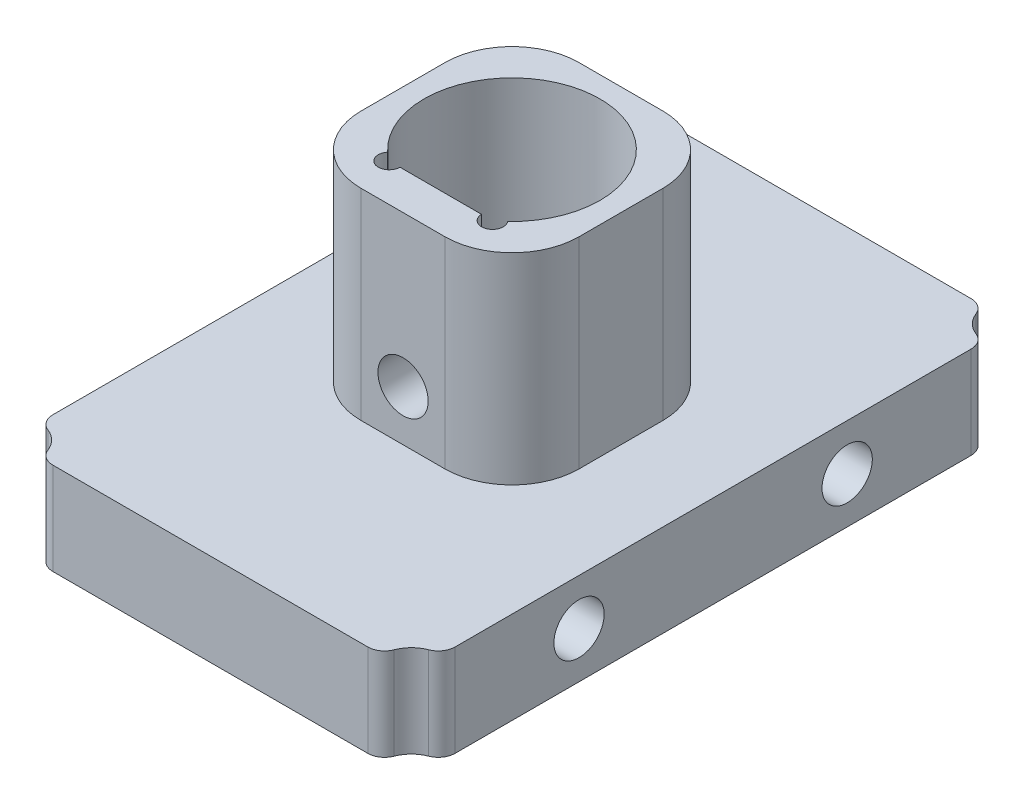
SolidWorks part; units mm, degrees
ref_plane "前视基准面" through (0, 0, 0) normal (0, 0, 1) x (1, 0, 0)
ref_plane "上视基准面" through (0, 0, 0) normal (0, 1, 0) x (1, 0, 0)
ref_plane "右视基准面" through (0, 0, 0) normal (1, 0, 0) x (0, 0, -1)
sketch "草图1" plane through (0, 0, 0) normal (0, 1, 0) x (1, 0, 0)
  line L0 (-2.4356, -4.25) -> (2.4356, -4.25)
  line L1 (-12, -18) -> (12, -18)
  line L2 (-12, -18) -> (-12, 18)
  line L3 (-12, 18) -> (12, 18)
  line L4 (12, -18) -> (12, 18)
  line L8 (-2.5, -6.5) -> (2.5, -6.5)
  line L9 (-6.5, -2.5) -> (-6.5, 2.5)
  line L10 (-2.5, 6.5) -> (2.5, 6.5)
  line L11 (6.5, -2.5) -> (6.5, 2.5)
  arc A0 (3.5813, -3.8389) -> (-3.5813, -3.8389) centre (0, 0) ccw
  arc A1 (-3.5813, -3.8389) -> (-2.4356, -4.25) centre (-3.0822, -4.25) ccw
  arc A2 (3.5813, -3.8389) -> (2.4356, -4.25) centre (3.0822, -4.25) cw
  arc A3 (-2.5, -6.5) -> (-6.5, -2.5) centre (-2.5, -2.5) cw
  arc A4 (-6.5, 2.5) -> (-2.5, 6.5) centre (-2.5, 2.5) cw
  arc A5 (6.5, 2.5) -> (2.5, 6.5) centre (2.5, 2.5) ccw
  arc A6 (6.5, -2.5) -> (2.5, -6.5) centre (2.5, -2.5) cw
  point P0 (0, 0)
  dimension "D1" = 4
extrude "凸台-拉伸1" add sketch "草图1" along normal blind 12 contours A6 L11 A5 L10 A4 L9 A3 L8 A0 A2 L0 A1
sketch "草图3" plane through (0, 0, 0) normal (0, -1, 0) x (1, 0, 0)
  line L0 (12, 15.3947) -> (12, -15.3947)
  line L1 (9.3947, -18) -> (-9.3947, -18)
  line L2 (-12, -15.3947) -> (-12, 15.3947)
  line L3 (-9.3947, 18) -> (9.3947, 18)
  arc A0 (11.3583, -16.3282) -> (10.3282, -17.3583) centre (12, -18) ccw
  arc A1 (-11.3583, -16.3282) -> (-10.3282, -17.3583) centre (-12, -18) cw
  arc A2 (-10.3282, 17.3583) -> (-11.3583, 16.3282) centre (-12, 18) cw
  arc A3 (10.3282, 17.3583) -> (11.3583, 16.3282) centre (12, 18) ccw
  arc A4 (12, 15.3947) -> (11.3583, 16.3282) centre (11, 15.3947) ccw
  arc A5 (10.3282, 17.3583) -> (9.3947, 18) centre (9.3947, 17) ccw
  arc A6 (10.3282, -17.3583) -> (9.3947, -18) centre (9.3947, -17) cw
  arc A7 (11.3583, -16.3282) -> (12, -15.3947) centre (11, -15.3947) ccw
  arc A8 (-12, 15.3947) -> (-11.3583, 16.3282) centre (-11, 15.3947) cw
  arc A9 (-10.3282, 17.3583) -> (-9.3947, 18) centre (-9.3947, 17) cw
  arc A10 (-9.3947, -18) -> (-10.3282, -17.3583) centre (-9.3947, -17) cw
  arc A11 (-11.3583, -16.3282) -> (-12, -15.3947) centre (-11, -15.3947) cw
  point P0 (0, 0)
  dimension "D1" = 1
  dimension "D2" = 1
  dimension "D3" = 1
extrude "凸台-拉伸3" add sketch "草图3" along normal blind 5.5
sketch "草图6" plane through (-12, 0, 0) normal (-1, 0, 0) x (0, 0, 1)
  line L0 (15.3947, -5.5) -> (-15.3947, -5.5) construction
  circle A0 centre (0, -2.75) radius 1.5
  circle A1 centre (8, -2.75) radius 1.5
  circle A2 centre (-8, -2.75) radius 1.5
  dimension "D1" = 2.75
  dimension "D2" = 2
  dimension "D3" = 2
extrude "切除-拉伸2" cut sketch "草图6" against normal blind 31
sketch "草图7" plane through (0, 0, 6.5) normal (0, 0, 1) x (1, 0, 0)
  line L0 (-2.5, 0) -> (2.5, 0) construction
  circle A0 centre (0, 3) radius 1.5
  dimension "D1" = 3
extrude "切除-拉伸3" cut sketch "草图7" against normal blind 31
sketch "草图8" plane through (0, -5.5, 0) normal (0, -1, 0) x (1, 0, 0)
  circle A0 centre (0, 0) radius 2.5
extrude "切除-拉伸5" cut sketch "草图8" against normal blind 31
sketch "草图9" plane through (12, 0, 0) normal (1, 0, 0) x (0, 0, -1)
  circle A0 centre (0, -2.75) radius 1.5
extrude "凸台-拉伸4" add sketch "草图9" against normal blind 24
sketch "草图10" plane through (0, -5.5, 0) normal (0, -1, 0) x (1, 0, 0)
  circle A0 centre (0, 0) radius 2.5
extrude "切除-拉伸6" cut sketch "草图10" against normal blind 24
